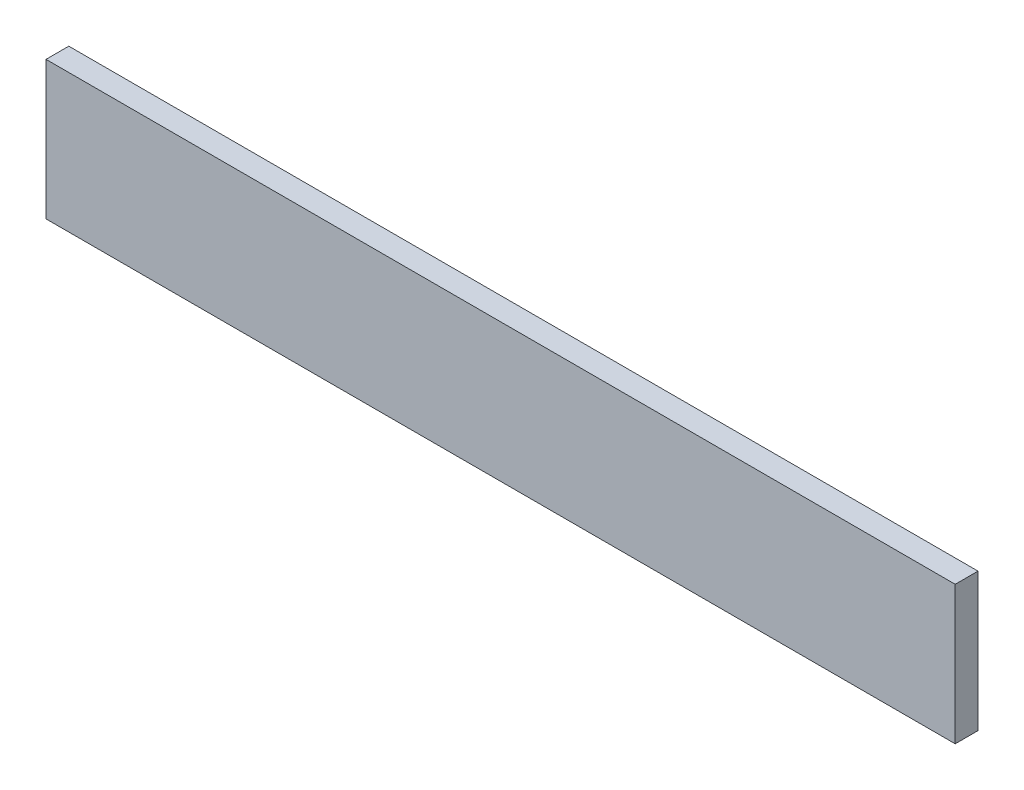
SolidWorks part; units mm, degrees
material "Pinho"
ref_plane "Plano frontal" through (0, 0, 0) normal (0, 0, 1) x (1, 0, 0)
ref_plane "Plano superior" through (0, 0, 0) normal (0, 1, 0) x (1, 0, 0)
ref_plane "Plano direito" through (0, 0, 0) normal (1, 0, 0) x (0, 0, -1)
sketch "Esboço1" plane through (0, 0, 0) normal (1, 0, 0) x (0, 0, -1)
  line L1 (-9.9, -60) -> (9.9, -60)
  line L2 (-9.9, -60) -> (-9.9, 60)
  line L3 (-9.9, 60) -> (9.9, 60)
  line L4 (9.9, -60) -> (9.9, 60)
  line L5 (-9.9, -60) -> (9.9, 60) construction
  line L6 (-9.9, 60) -> (9.9, -60) construction
  point P0 (0, 0)
  dimension "D1" = 19.8
  dimension "D2" = 120
extrude "Ressalto-extrusão1" add sketch "Esboço1" against normal blind 789.6
